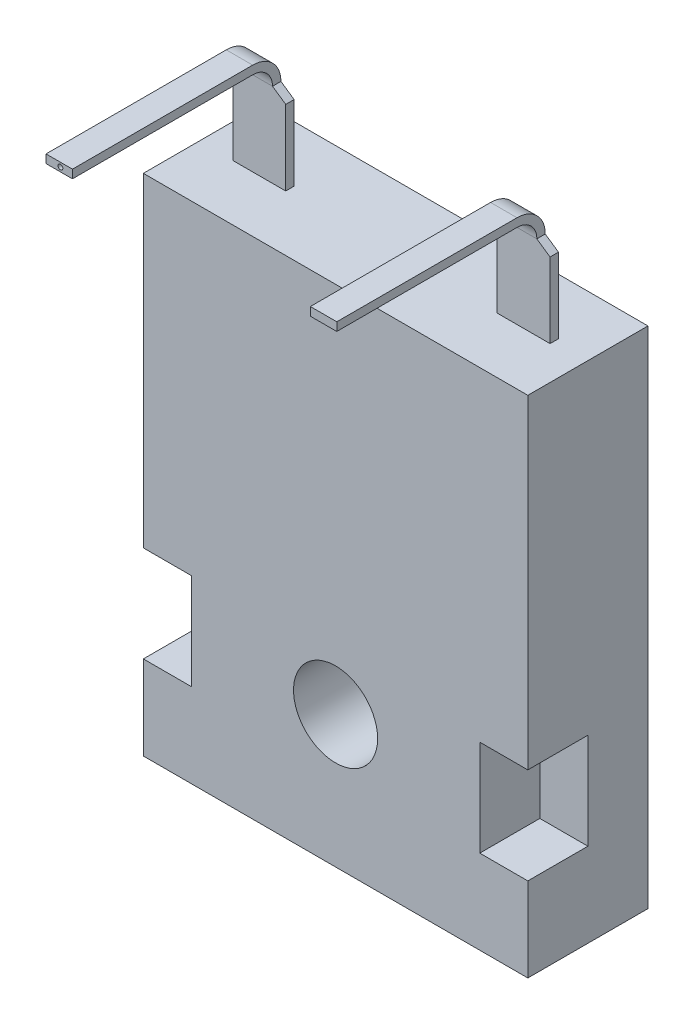
SolidWorks part; units mm, degrees
ref_plane "Спереди" through (0, 0, 0) normal (0, 0, 1) x (1, 0, 0)
ref_plane "Сверху" through (0, 0, 0) normal (0, 1, 0) x (1, 0, 0)
ref_plane "Справа" through (0, 0, 0) normal (1, 0, 0) x (0, 0, -1)
sketch "Эскиз1" plane through (0, 0, 0) normal (0, 0, 1) x (1, 0, 0)
  line L0 (0, -19.3209) -> (0, 33.6087) construction
  line L1 (-32.3098, 0) -> (29.0626, 0) construction
  line L3 (-8, -5.5) -> (8, -5.5)
  line L4 (-8, -5.5) -> (-8, 15.5)
  line L5 (-8, 15.5) -> (8, 15.5)
  line L6 (8, -5.5) -> (8, 15.5)
  circle A0 centre (0, 0) radius 1.75
  dimension "D4" = 3.5
  dimension "D1" = 16
  dimension "D2" = 21
  dimension "D3" = 11
extrude "Вытянуть1" add sketch "Эскиз1" along normal blind 5
sketch "Эскиз2" plane through (-8, 0, 0) normal (-1, 0, 0) x (0, 0, 1)
  line L0 (2.5, 7.3644) -> (2.5, 25.6142) construction
  line L1 (0, 15.5) -> (0, -5.5) construction
  line L2 (5, 15.5) -> (5, -5.5) construction
  line L3 (2.5, 15.5) -> (2.5, 19)
  line L4 (5, 15.5) -> (0, 15.5) construction
  line L6 (3.5, 20) -> (11, 20)
  arc A1 (2.5, 19) -> (3.5, 20) centre (3.5, 19) cw
  point P14 (2.5, 20)
  dimension "D2" = 11
  dimension "D1" = 1
  dimension "D3" = 20
extrude "Вытянуть-Тонкостенный1" add sketch "Эскиз2" against normal blind 16 thin thin type mid plane wall 0.35
sketch "Эскиз3" plane through (0, 0, 2.325) normal (0, 0, -1) x (-1, 0, 0)
  line L0 (0, 0) -> (0, 22.5231) construction
  line L1 (-1.75, 15.5) -> (-1.75, 18.5)
  line L2 (-8, 15.5) -> (8, 15.5) construction
  line L3 (-1.75, 18.5) -> (-0.55, 19)
  line L4 (-0.55, 19) -> (-0.55, 20.9379)
  line L5 (-8, 19) -> (8, 19) construction
  line L6 (0.55, 19) -> (0.55, 20.9379)
  line L7 (1.75, 18.5) -> (0.55, 19)
  line L8 (1.75, 15.5) -> (1.75, 18.5)
  line L9 (-5.5, 14.4406) -> (-5.5, 21.8466) construction
  line L10 (-4.95, 19) -> (-4.4, 18.6221)
  line L11 (-6.05, 19) -> (-6.05, 20.9379)
  line L12 (-6.05, 19) -> (-6.6, 18.6221)
  line L13 (-6.6, 18.6221) -> (-6.6, 15.5)
  line L14 (-4.95, 19) -> (-4.95, 20.9379)
  line L15 (-4.4, 18.6221) -> (-4.4, 15.5)
  line L16 (4.4, 18.6221) -> (4.4, 15.5)
  line L17 (4.95, 19) -> (4.4, 18.6221)
  line L18 (4.95, 19) -> (4.95, 20.9379)
  line L19 (6.05, 19) -> (6.05, 20.9379)
  line L20 (6.05, 19) -> (6.6, 18.6221)
  line L21 (6.6, 18.6221) -> (6.6, 15.5)
  line L22 (1.75, 15.5) -> (4.4, 15.5)
  line L23 (0.55, 20.9379) -> (4.95, 20.9379)
  line L24 (-0.55, 20.9379) -> (-4.95, 20.9379)
  line L25 (-6.6, 15.5) -> (-9.3209, 15.5)
  line L26 (-9.3209, 15.5) -> (-9.3209, 20.9379)
  line L27 (-9.3209, 20.9379) -> (-6.05, 20.9379)
  line L28 (6.05, 20.9379) -> (9.4998, 20.9379)
  line L29 (9.4998, 20.9379) -> (9.4998, 15.5)
  line L30 (9.4998, 15.5) -> (6.6, 15.5)
  line L31 (-4.4, 15.5) -> (-1.75, 15.5)
  dimension "D1" = 3
  dimension "D2" = 1.1
  dimension "D3" = 3.5
  dimension "D4" = 5.5
  dimension "D5" = 1.1
  dimension "D6" = 1.1
extrude "Вырез-Вытянуть1" cut sketch "Эскиз3" against normal blind 16
sketch "Эскиз4" plane through (0, 0, 5) normal (0, 0, -1) x (-1, 0, 0)
  line L0 (-11.0027, 0) -> (9.7903, 0) construction
  line L1 (0, 0) -> (0, 8.7015) construction
  line L2 (6, -2) -> (9.8191, -2)
  line L3 (6, -2) -> (6, 2)
  line L4 (6, 2) -> (9.8191, 2)
  line L5 (9.8191, -2) -> (9.8191, 2)
  line L6 (8, 15.5) -> (8, -5.5) construction
  line L7 (-9.8191, -2) -> (-9.8191, 2)
  line L8 (-6, 2) -> (-9.8191, 2)
  line L9 (-6, -2) -> (-6, 2)
  line L10 (-6, -2) -> (-9.8191, -2)
  dimension "D1" = 2
  dimension "D2" = 4
extrude "Вырез-Вытянуть2" cut sketch "Эскиз4" along normal blind 2.5
sketch "Эскиз5" plane through (0, 0, 11) normal (0, 0, 1) x (1, 0, 0)
  line L0 (0, 0) -> (0, 21.3988) construction
  line L1 (-6.7561, 20) -> (1.1243, 20) construction
  line L2 (0.55, 20.175) -> (-0.55, 20.175) construction
  line L3 (0.55, 19.825) -> (-0.55, 19.825) construction
  circle A1 centre (-5.45, 20) radius 0.1
  dimension "D1" = 5.45
  dimension "D2" = 0.2
extrude "Вырез-Вытянуть3" cut sketch "Эскиз5" against normal blind 2
sketch "Эскиз6" plane through (0, 0, 2.325) normal (0, 0, -1) x (-1, 0, 0)
  line L0 (-8, 15.5) -> (8, 15.5) construction
  line L1 (-2.726, 15.5) -> (3.427, 15.5)
  line L2 (-2.726, 15.5) -> (-2.726, 21.5324)
  line L3 (-2.726, 21.5324) -> (3.427, 21.5324)
  line L4 (3.427, 15.5) -> (3.427, 21.5324)
extrude "Вырез-Вытянуть4" cut sketch "Эскиз6" against normal blind 10
